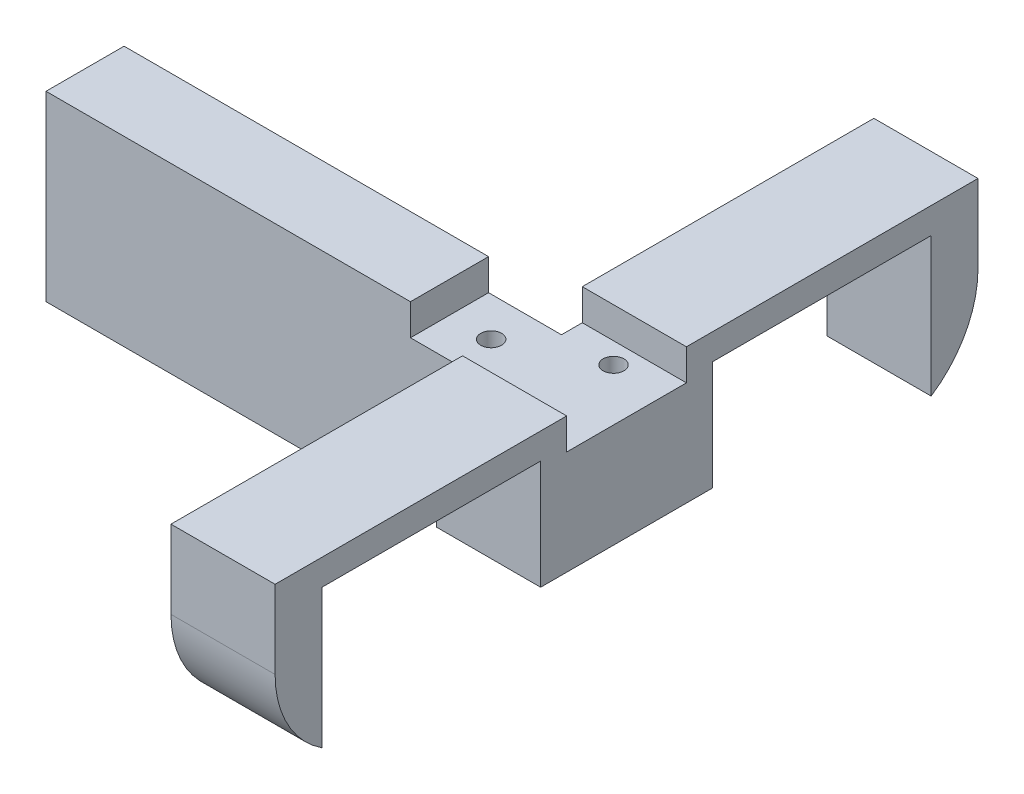
SolidWorks part; units mm, degrees
ref_plane "Front Plane" through (0, 0, 0) normal (0, 0, 1) x (1, 0, 0)
ref_plane "Top Plane" through (0, 0, 0) normal (0, 1, 0) x (1, 0, 0)
ref_plane "Right Plane" through (0, 0, 0) normal (1, 0, 0) x (0, 0, -1)
sketch "Sketch1" plane through (0, 0, 0) normal (0, 1, 0) x (1, 0, 0)
  line L1 (-38.3176, 43.2333) -> (45.6824, 43.2333)
  line L2 (45.6824, 43.2333) -> (45.6824, -16.7667)
  line L3 (45.6824, -16.7667) -> (65.6824, -16.7667)
  line L4 (65.6824, -16.7667) -> (65.6824, 118.2333)
  line L7 (-38.3176, 43.2333) -> (-38.3176, 58.2333)
  line L8 (-38.3176, 58.2333) -> (45.6824, 58.2333)
  line L9 (45.6824, 58.2333) -> (45.6824, 118.2333)
  line L10 (45.6824, 118.2333) -> (65.6824, 118.2333)
  dimension "D1" = 20
  dimension "D2" = 60
  dimension "D3" = 84
  dimension "D4" = 15
  dimension "D5" = 60
  dimension "D6" = 20
extrude "Boss-Extrude1" add sketch "Sketch1" along normal blind 35
sketch "Sketch2" plane through (65.6824, 0, 0) normal (1, 0, 0) x (0, 0, -1)
  line L1 (-7.7667, 30) -> (34.2333, 30)
  line L2 (-7.7667, 30) -> (-7.7667, 9)
  line L3 (-7.7667, 9) -> (34.2333, 9)
  line L4 (34.2333, 30) -> (34.2333, 9)
  line L5 (-16.7667, 35) -> (-16.7667, 0) construction
  line L6 (50.7333, 24.6294) -> (50.7333, 59.3446) construction
  line L7 (-16.7667, 0) -> (118.2333, 0) construction
  line L9 (109.2333, 9) -> (67.2333, 9)
  line L10 (109.2333, 30) -> (109.2333, 9)
  line L11 (109.2333, 30) -> (67.2333, 30)
  line L12 (67.2333, 30) -> (67.2333, 9)
  dimension "D1" = 21
  dimension "D2" = 42
  dimension "D3" = 9
  dimension "D4" = 9
  dimension "D5" = 7.5
extrude "Cut-Extrude1" cut sketch "Sketch2" against normal up to next
sketch "Sketch3" plane through (45.6824, 0, 0) normal (-1, 0, 0) x (0, 0, 1)
  line L0 (7.7667, 9) -> (7.7667, 30) construction
  line L1 (-34.2333, 9) -> (7.7667, 9) construction
  line L2 (-50.7333, 32.1987) -> (-50.7333, 60.1119) construction
  line L3 (-43.2333, 35) -> (-43.2333, 0) construction
  circle A0 centre (11.2667, 24.75) radius 2
  circle A1 centre (11.2667, 15.25) radius 2
  circle A2 centre (-37.7333, 24.75) radius 2
  circle A3 centre (-37.7333, 15.25) radius 2
  circle A4 centre (-112.7333, 24.75) radius 2
  circle A5 centre (-112.7333, 15.25) radius 2
  circle A6 centre (-63.7333, 15.25) radius 2
  circle A7 centre (-63.7333, 24.75) radius 2
  dimension "D1" = 4
  dimension "D2" = 49
  dimension "D3" = 9.5
  dimension "D4" = 3.5
  dimension "D5" = 6.25
  dimension "D6" = 7.5
extrude "Cut-Extrude2" cut sketch "Sketch3" against normal blind 10
fillet "Fillet1" radius 20 2 edges at (55.6824, 0, 16.7667) (55.6824, 0, -118.2333)
sketch "Sketch6" plane through (65.6824, 0, 0) normal (1, 0, 0) x (0, 0, -1)
  line L0 (34.2333, 9) -> (34.2333, 30) construction
  line L1 (-7.7667, 9) -> (34.2333, 9)
  line L2 (-7.7667, 9) -> (-7.7667, 0)
  line L3 (-7.7667, 0) -> (34.2333, 0)
  line L4 (34.2333, 9) -> (34.2333, 0)
  line L5 (3.2333, 0) -> (98.2333, 0) construction
  line L6 (50.7333, 24.0053) -> (50.7333, 51.0852) construction
  line L7 (67.2333, 9) -> (67.2333, 0)
  line L8 (109.2333, 9) -> (67.2333, 9)
  line L9 (109.2333, 0) -> (67.2333, 0)
  line L10 (109.2333, 9) -> (109.2333, 0)
  dimension "D1" = 7.5
extrude "Cut-Extrude5" cut sketch "Sketch6" against normal up to next
sketch "Sketch7" plane through (-38.3176, 0, 0) normal (-1, 0, 0) x (0, 0, 1)
  line L2 (-58.2333, 35) -> (-43.2333, 35) construction
  line L3 (-43.2333, 35) -> (-43.2333, 0) construction
  circle A0 centre (-50.7333, 25) radius 2
  circle A1 centre (-50.7333, 10) radius 2
  dimension "D1" = 4
  dimension "D3" = 15
  dimension "D4" = 10
  dimension "D5" = 7.5
extrude "Cut-Extrude6" cut sketch "Sketch7" against normal blind 10
sketch "Sketch8" plane through (0, 0, 0) normal (0, -1, 0) x (1, 0, 0)
  line L1 (45.6824, -67.2333) -> (45.6824, -58.2333) construction
  line L2 (45.6824, -67.2333) -> (65.6824, -67.2333) construction
  line L3 (65.6824, -34.2333) -> (65.6824, -67.2333) construction
  line L4 (45.6824, -34.2333) -> (65.6824, -34.2333) construction
  line L5 (45.6824, -43.2333) -> (45.6824, -34.2333) construction
  line L9 (45.6824, -67.2333) -> (45.6824, -58.2333)
  line L10 (45.6824, -67.2333) -> (65.6824, -67.2333)
  line L11 (65.6824, -34.2333) -> (65.6824, -67.2333)
  line L12 (45.6824, -34.2333) -> (65.6824, -34.2333)
  line L13 (45.6824, -43.2333) -> (45.6824, -34.2333)
  line L16 (45.6824, -43.2333) -> (25.6824, -43.2333)
  line L17 (-38.3176, -43.2333) -> (45.6824, -43.2333) construction
  line L18 (25.6824, -43.2333) -> (25.6824, -58.2333)
  line L19 (45.6824, -58.2333) -> (-38.3176, -58.2333) construction
  line L20 (25.6824, -58.2333) -> (45.6824, -58.2333)
  dimension "D1" = 20
extrude "Cut-Extrude7" cut sketch "Sketch8" against normal blind 9
sketch "Sketch9" plane through (0, 9, 0) normal (0, -1, 0) x (1, 0, 0)
  line L0 (25.6824, -58.2333) -> (45.6824, -58.2333) construction
  line L1 (65.6824, -34.2333) -> (45.6824, -34.2333) construction
  line L2 (65.6824, -67.2333) -> (65.6824, -34.2333) construction
  line L3 (45.6824, -67.2333) -> (65.6824, -67.2333) construction
  circle A0 centre (55.6824, -42.2333) radius 2
  circle A1 centre (55.6824, -59.2333) radius 2
  circle A2 centre (35.6824, -50.7333) radius 2
  dimension "D1" = 4
  dimension "D2" = 7.5
  dimension "D3" = 30
  dimension "D4" = 10
  dimension "D5" = 8
  dimension "D6" = 8
extrude "Cut-Extrude8" cut sketch "Sketch9" against normal blind 10
sketch "Sketch10" plane through (0, 35, 0) normal (0, 1, 0) x (1, 0, 0)
  line L0 (45.6824, 62.2333) -> (65.6824, 62.2333)
  line L1 (45.6824, 118.2333) -> (45.6824, 58.2333) construction
  line L2 (65.6824, -16.7667) -> (65.6824, 118.2333) construction
  line L3 (65.6824, 62.2333) -> (65.6824, 39.2333)
  line L4 (65.6824, 39.2333) -> (45.6824, 39.2333)
  line L5 (45.6824, 43.2333) -> (45.6824, -16.7667) construction
  line L7 (45.6824, 39.2333) -> (45.6824, 43.2333)
  line L8 (45.6824, 43.2333) -> (31.6824, 43.2333)
  line L9 (-38.3176, 43.2333) -> (45.6824, 43.2333) construction
  line L10 (31.6824, 43.2333) -> (31.6824, 58.2333)
  line L11 (45.6824, 58.2333) -> (-38.3176, 58.2333) construction
  line L12 (31.6824, 58.2333) -> (45.6824, 58.2333)
  line L13 (45.6824, 58.2333) -> (45.6824, 62.2333)
  dimension "D1" = 5
  dimension "D2" = 5
  dimension "D3" = 14
extrude "Cut-Extrude9" cut sketch "Sketch10" against normal blind 6
sketch "Sketch11" plane through (0, 29, 0) normal (0, 1, 0) x (1, 0, 0)
  line L0 (45.6824, 62.2333) -> (45.6824, 58.2333) construction
  line L1 (45.6824, 58.2333) -> (31.6824, 58.2333) construction
  circle A0 centre (55.6824, 58.2333) radius 2
  circle A1 centre (55.6824, 43.2333) radius 2
  circle A2 centre (39.6824, 50.7333) radius 2
  dimension "D1" = 4
  dimension "D2" = 10
  dimension "D3" = 7.5
  dimension "D4" = 6
  dimension "D5" = 0
extrude "Cut-Extrude10" cut sketch "Sketch11" against normal blind 9
